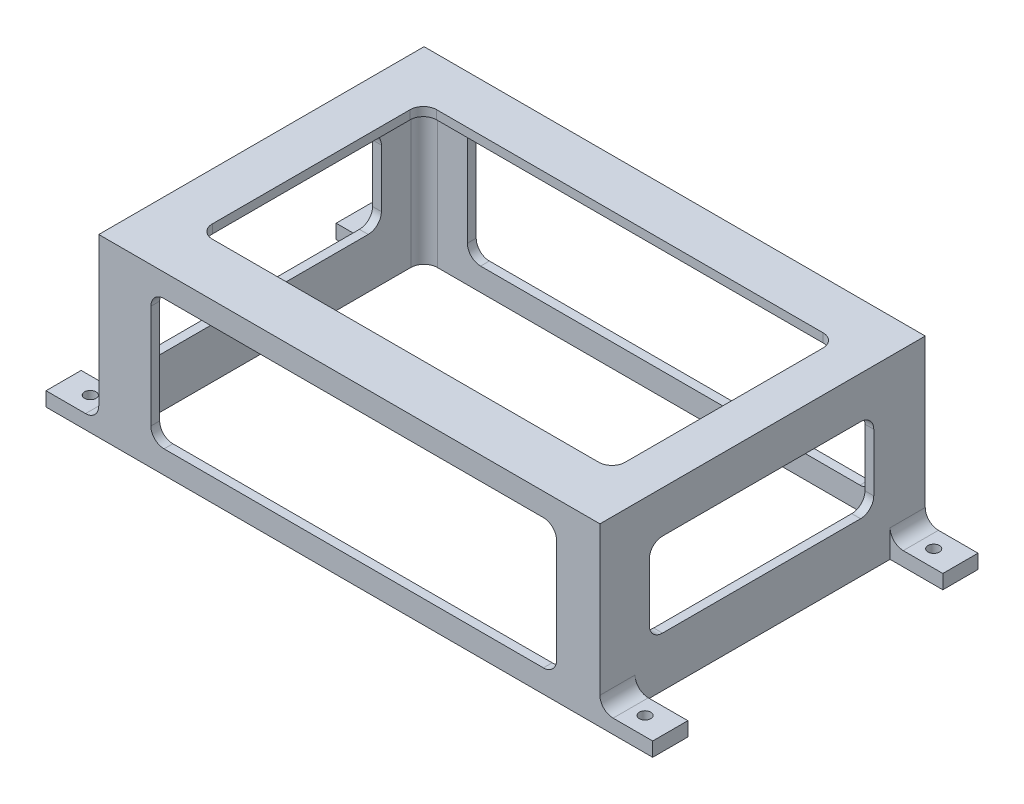
SolidWorks part; units mm, degrees
ref_plane "Front Plane" through (0, 0, 0) normal (0, 0, 1) x (1, 0, 0)
ref_plane "Top Plane" through (0, 0, 0) normal (0, 1, 0) x (1, 0, 0)
ref_plane "Right Plane" through (0, 0, 0) normal (1, 0, 0) x (0, 0, -1)
sketch "Sketch1" plane through (0, 0, 0) normal (0, 1, 0) x (1, 0, 0)
  line L1 (-57, 37) -> (57, 37)
  line L2 (-57, 37) -> (-57, -37)
  line L3 (-57, -37) -> (57, -37)
  line L4 (57, 37) -> (57, -37)
  line L5 (0, -37) -> (0, 37) construction
  line L6 (-57, 0) -> (57, 0) construction
  point P0 (0, 0)
  dimension "D1" = 74
  dimension "D2" = 114
extrude "Boss-Extrude1" add sketch "Sketch1" along normal blind 40
shell "Shell1" thickness 2
sketch "Sketch2" plane through (-57, 0, 0) normal (-1, 0, 0) x (0, 0, 1)
  line L1 (-37, 0) -> (-29, 0)
  line L2 (-37, 0) -> (-37, 3.2242)
  line L3 (-37, 3.2242) -> (-29, 3.2242)
  line L4 (-29, 0) -> (-29, 3.2242)
  line L5 (37, 0) -> (29, 0)
  line L6 (37, 0) -> (37, 3.2242)
  line L7 (37, 3.2242) -> (29, 3.2242)
  line L8 (29, 0) -> (29, 3.2242)
  dimension "D1" = 8
  dimension "D2" = 8
extrude "Boss-Extrude2" add sketch "Sketch2" along normal blind 12
ref_plane "Plane1" through (0, 0, 0) normal (-1, 0, 0) x (0, 0, 1)
mirror "Mirror1" about plane through (0, 0, 0) normal (-1, 0, 0) of "Boss-Extrude2"
sketch "Sketch3" plane through (0, 40, 0) normal (0, 1, 0) x (1, 0, 0)
  line L0 (57, 37) -> (-57, -37) construction
  line L1 (-57, 37) -> (-57, -37) construction
  line L2 (-57, -37) -> (57, -37) construction
  line L4 (47.7378, -25.0012) -> (-46.1748, -25.0012)
  line L5 (47.7378, -25.0012) -> (47.7378, 26.0158)
  line L6 (47.7378, 26.0158) -> (-46.1748, 26.0158)
  line L7 (-46.1748, -25.0012) -> (-46.1748, 26.0158)
  line L8 (0.7815, 26.0158) -> (0.7815, -25.0012) construction
  line L9 (47.7378, 0.5073) -> (-46.1748, 0.5073) construction
  point P7 (0.7815, 0.5073)
extrude "Cut-Extrude1" cut sketch "Sketch3" against normal up to next
sketch "Sketch4" plane through (-57, 0, 0) normal (-1, 0, 0) x (0, 0, 1)
  line L0 (-37, 40) -> (37.4756, 1.8324) construction
  line L2 (-25.2888, 30.4673) -> (25.7644, 30.4673)
  line L3 (-25.2888, 30.4673) -> (-25.2888, 11.3651)
  line L4 (-25.2888, 11.3651) -> (25.7644, 11.3651)
  line L5 (25.7644, 30.4673) -> (25.7644, 11.3651)
  line L6 (0.2378, 11.3651) -> (0.2378, 30.4673) construction
  line L7 (-25.2888, 20.9162) -> (25.7644, 20.9162) construction
  point P3 (0.2378, 20.9162)
extrude "Cut-Extrude2" cut sketch "Sketch4" against normal through all
sketch "Sketch5" plane through (0, 0, 37) normal (0, 0, 1) x (1, 0, 0)
  line L0 (-57, 40) -> (59, 0) construction
  line L1 (-69, 0) -> (69, 0) construction
  line L3 (-45.1442, 34.7991) -> (47.1442, 34.7991)
  line L4 (-45.1442, 34.7991) -> (-45.1442, 5.2009)
  line L5 (-45.1442, 5.2009) -> (47.1442, 5.2009)
  line L6 (47.1442, 34.7991) -> (47.1442, 5.2009)
  line L7 (1, 5.2009) -> (1, 34.7991) construction
  line L8 (-45.1442, 20) -> (47.1442, 20) construction
  point P5 (1, 20)
extrude "Cut-Extrude3" cut sketch "Sketch5" against normal through all
sketch "Sketch6" plane through (-57, 0, 0) normal (-1, 0, 0) x (0, 0, 1)
  line L0 (25.7644, 30.4673) -> (30.0927, 30.4673)
  line L1 (30.0927, 30.4673) -> (30.0927, 11.3651)
  line L2 (30.0927, 11.3651) -> (25.7644, 11.3651)
  line L3 (25.7644, 11.3651) -> (25.7644, 30.4673)
extrude "Cut-Extrude4" cut sketch "Sketch6" against normal blind 12
fillet "Fillet1" radius 3 32 edges at (47.7378, 39, -26.0158) (-46.1748, 39, -26.0158) (-46.1748, 39, 25.0012) (47.7378, 39, 25.0012) (56, 11.3651, 25.7644) (56, 30.4673, 25.7644) (56, 30.4673, -25.2888) (56, 11.3651, -25.2888) (-45.1442, 5.2009, -36) (-45.1442, 34.7991, -36) (-56, 30.4673, 30.0927) (-56, 11.3651, 30.0927) (-56, 11.3651, -25.2888) (-56, 30.4673, -25.2888) (47.1442, 34.7991, -36) (47.1442, 34.7991, 36) (47.1442, 5.2009, -36) (47.1442, 5.2009, 36) (-45.1442, 5.2009, 36) (-45.1442, 34.7991, 36) (57, 3.2242, 33) (57, 3.2242, -33) (-57, 3.2242, -33) (-57, 3.2242, 33) (0, 38, 35) (-55, 38, 0) (0, 38, -35) (55, 38, 0) (55, 19, 35) (55, 19, -35) (-55, 19, -35) (-55, 19, 35)
sketch "Sketch7" plane through (0, 0, 0) normal (0, -1, 0) x (1, 0, 0)
  line L1 (-63.1, -32.825) -> (63.1, -32.825) construction
  line L2 (-63.1, -32.825) -> (-63.1, 32.825) construction
  line L3 (-63.1, 32.825) -> (63.1, 32.825) construction
  line L4 (63.1, -32.825) -> (63.1, 32.825) construction
  line L5 (0, 32.825) -> (0, -32.825) construction
  line L6 (-63.1, 0) -> (63.1, 0) construction
  circle A0 centre (-63.1, -32.825) radius 1.3
  circle A1 centre (-63.1, 32.825) radius 1.3
  circle A2 centre (63.1, 32.825) radius 1.3
  circle A3 centre (63.1, -32.825) radius 1.3
  point P0 (0, 0)
  dimension "D1" = 65.65
  dimension "D2" = 126.2
extrude "Cut-Extrude5" cut sketch "Sketch7" against normal blind 12
